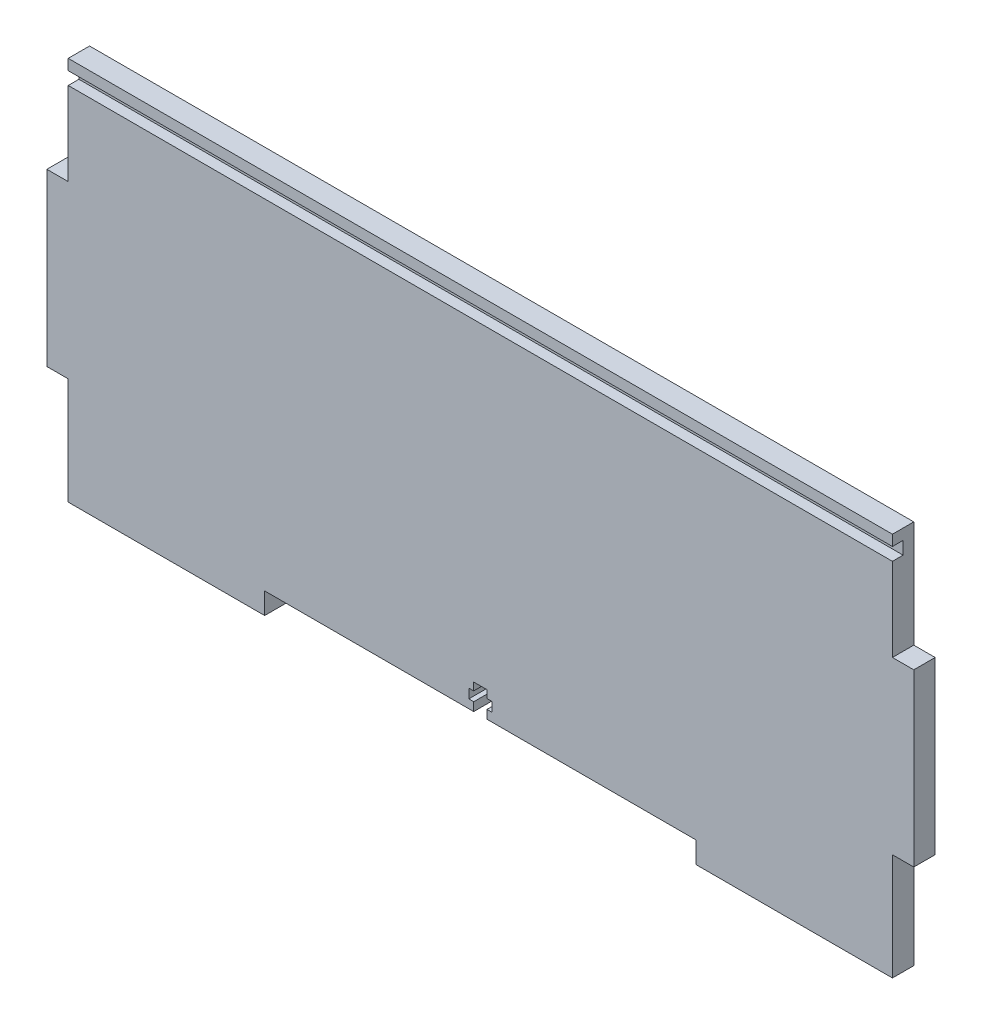
SolidWorks part; units mm, degrees
ref_plane "Front Plane" through (0, 0, 0) normal (0, 0, 1) x (1, 0, 0)
ref_plane "Top Plane" through (0, 0, 0) normal (0, 1, 0) x (1, 0, 0)
ref_plane "Right Plane" through (0, 0, 0) normal (1, 0, 0) x (0, 0, -1)
sketch "Sketch1" plane through (0, 0, 0) normal (0, 0, 1) x (1, 0, 0)
  line L1 (0, 0) -> (203, 0)
  line L2 (0, 0) -> (0, 90)
  line L3 (0, 90) -> (203, 90)
  line L4 (203, 0) -> (203, 90)
  dimension "D1" = 90
  dimension "D2" = 203
extrude "Boss-Extrude1" add sketch "Sketch1" along normal blind 5
sketch "Sketch3" plane through (0, 0, 5) normal (0, 0, 1) x (1, 0, 0)
  line L0 (0, 90) -> (0, 0) construction
  line L1 (0, 25) -> (5, 25)
  line L2 (0, 25) -> (0, 0)
  line L3 (0, 0) -> (5, 0)
  line L4 (5, 25) -> (5, 0)
  line L5 (0, 0) -> (203, 0) construction
  line L6 (203, 0) -> (203, 90) construction
  line L7 (0, 65) -> (5, 65)
  line L8 (0, 65) -> (0, 90)
  line L9 (0, 90) -> (5, 90)
  line L10 (5, 65) -> (5, 90)
  line L11 (203, 0) -> (198, 0)
  line L12 (203, 0) -> (203, 25)
  line L13 (203, 25) -> (198, 25)
  line L14 (198, 0) -> (198, 25)
  line L15 (203, 65) -> (198, 65)
  line L16 (203, 65) -> (203, 90)
  line L17 (203, 90) -> (198, 90)
  line L18 (198, 65) -> (198, 90)
  line L20 (51, 0) -> (152, 0)
  line L21 (51, 0) -> (51, 5)
  line L22 (51, 5) -> (152, 5)
  line L23 (152, 0) -> (152, 5)
  dimension "D1" = 5
  dimension "D2" = 25
  dimension "D3" = 0
  dimension "D4" = 5
  dimension "D5" = 25
  dimension "D6" = 65
  dimension "D7" = 5
  dimension "D8" = 5
  dimension "D9" = 101
  dimension "D10" = 51
  dimension "D11" = 5
  dimension "D12" = 25
  dimension "D13" = 65
extrude "Cut-Extrude2" cut sketch "Sketch3" against normal through all
sketch "Sketch4" plane through (0, 0, 5) normal (0, 0, 1) x (1, 0, 0)
  line L0 (5, 65) -> (5, 90) construction
  line L1 (5, 87.5) -> (198, 87.5)
  line L2 (5, 87.5) -> (5, 84.5)
  line L3 (5, 84.5) -> (198, 84.5)
  line L4 (198, 87.5) -> (198, 84.5)
  line L5 (198, 90) -> (198, 65) construction
  line L6 (198, 90) -> (5, 90) construction
  dimension "D1" = 193
  dimension "D2" = 3
  dimension "D3" = 2.5
extrude "Cut-Extrude3" cut sketch "Sketch4" against normal blind 2.5
sketch "Sketch5" plane through (0, 0, 5) normal (0, 0, 1) x (1, 0, 0)
  line L0 (152, 5) -> (51, 5) construction
  line L1 (51, 5) -> (51, 0) construction
  line L4 (103.05, 11) -> (99.95, 11)
  line L5 (103.05, 11) -> (103.05, 5)
  line L6 (103.05, 5) -> (99.95, 5)
  line L7 (99.95, 11) -> (99.95, 5)
  line L12 (104.2, 7) -> (98.8, 7)
  line L13 (104.2, 7) -> (104.2, 9.2)
  line L14 (104.2, 9.2) -> (98.8, 9.2)
  line L15 (98.8, 7) -> (98.8, 9.2)
  line M15 (51, 5) -> (152, 5)
  dimension "D1" = 3.1
  dimension "D2" = 5.4
  dimension "D3" = 2.2
  dimension "D4" = 6
  dimension "D5" = 1.8
  dimension "D6" = 1.15
  dimension "D7" = 0
  dimension "D8" = 48.95
extrude "Cut-Extrude4" cut sketch "Sketch5" against normal through all contours L14 L5 L4 L7 | L5 L14 L7 L12 | L15 L12 L7 L14 | L13 L14 L5 L12 | L5 L12 L7 M15
equation "\"D8@Sketch5\"=(101-3.1)/2"
equation "\"D10@Sketch3\"=(203-101)/2"
